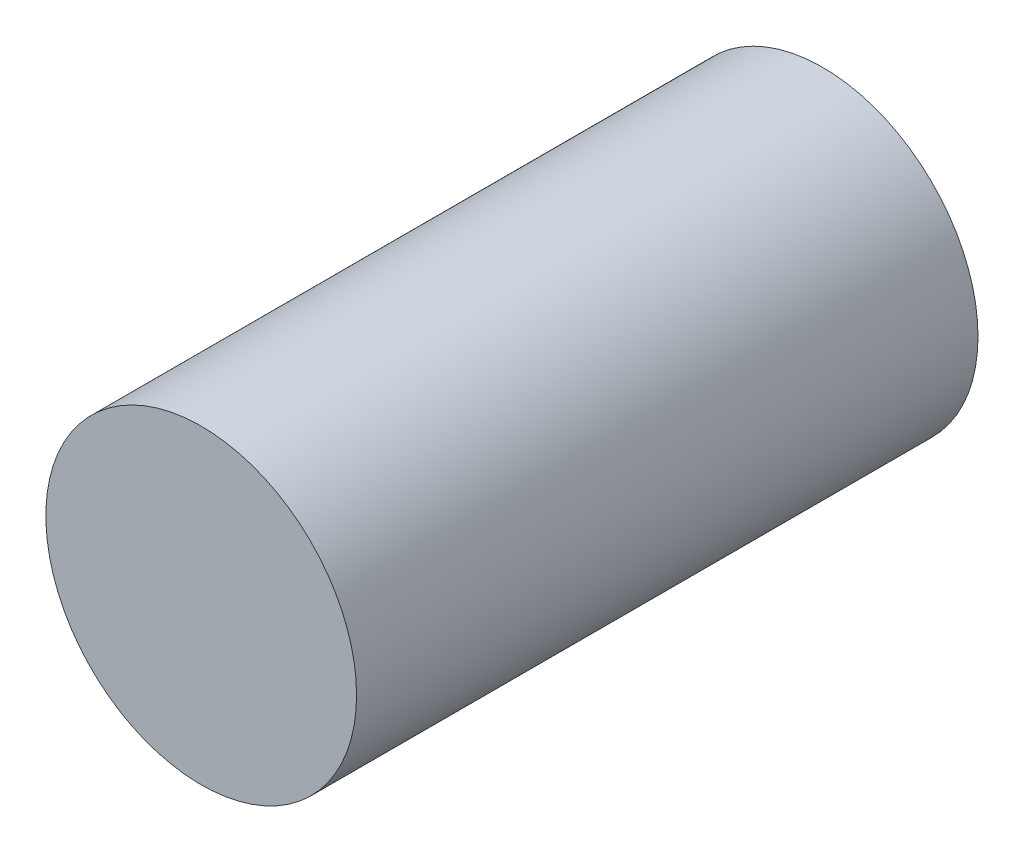
SolidWorks part; units mm, degrees
ref_plane "Front Plane" through (0, 0, 0) normal (0, 0, 1) x (1, 0, 0)
ref_plane "Top Plane" through (0, 0, 0) normal (0, 1, 0) x (1, 0, 0)
ref_plane "Right Plane" through (0, 0, 0) normal (1, 0, 0) x (0, 0, -1)
sketch "Sketch1" plane through (0, 0, 0) normal (0, 0, 1) x (1, 0, 0)
  circle A0 centre (0, 0) radius 10
extrude "Boss-Extrude1" add sketch "Sketch1" along normal blind 40
